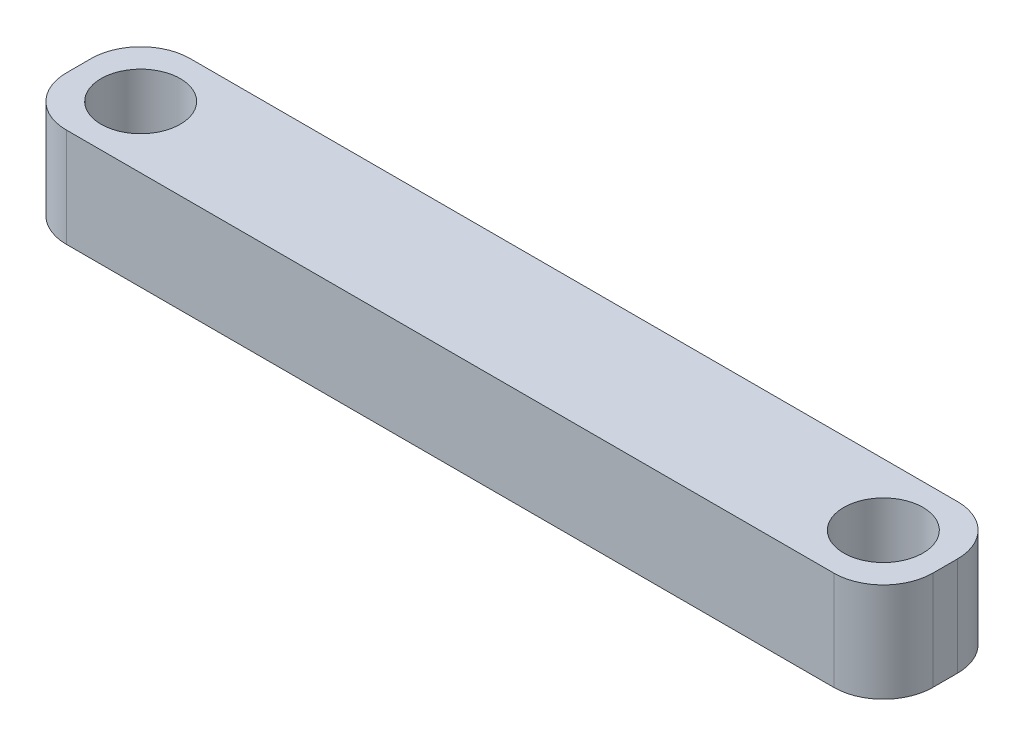
SolidWorks part; units mm, degrees
ref_plane "前视基准面" through (0, 0, 0) normal (0, 0, 1) x (1, 0, 0)
ref_plane "上视基准面" through (0, 0, 0) normal (0, 1, 0) x (1, 0, 0)
ref_plane "右视基准面" through (0, 0, 0) normal (1, 0, 0) x (0, 0, -1)
sketch "草图1" plane through (0, 0, 0) normal (0, 1, 0) x (1, 0, 0)
  line L0 (0, -55) -> (0, 55) construction
  line L1 (-17.5, 2.5) -> (17.5, 2.5)
  line L2 (-17.5, 2.5) -> (-17.5, -2.5)
  line L3 (-17.5, -2.5) -> (17.5, -2.5)
  line L4 (17.5, 2.5) -> (17.5, -2.5)
  line L5 (-17.5, 2.5) -> (17.5, -2.5) construction
  line L6 (-17.5, -2.5) -> (17.5, 2.5) construction
  circle A0 centre (-15, 0) radius 1.6
  circle A1 centre (15, 0) radius 1.6
  point P0 (0, 0)
  dimension "D1" = 3.2
  dimension "D2" = 5
  dimension "D3" = 15
  dimension "D4" = 2.5
extrude "凸台-拉伸1" add sketch "草图1" along normal blind 4
fillet "圆角1" radius 2 4 edges at (17.5, 2, 2.5) (17.5, 2, -2.5) (-17.5, 2, -2.5) (-17.5, 2, 2.5)
